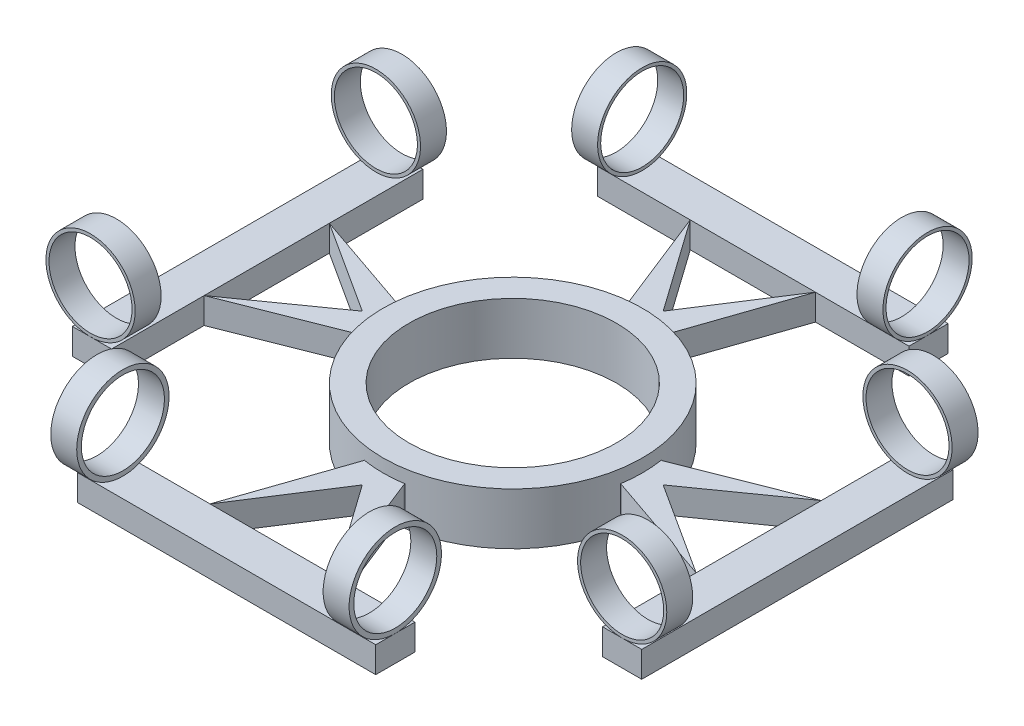
SolidWorks part; units mm, degrees
ref_plane "Front Plane" through (0, 0, 0) normal (0, 0, 1) x (1, 0, 0)
ref_plane "Top Plane" through (0, 0, 0) normal (0, 1, 0) x (1, 0, 0)
ref_plane "Right Plane" through (0, 0, 0) normal (1, 0, 0) x (0, 0, -1)
sketch "Sketch1" plane through (0, 0, 0) normal (0, 1, 0) x (1, 0, 0)
  circle A0 centre (0, 0) radius 2
  circle A1 centre (0, 0) radius 2.5
extrude "Boss-Extrude1" add sketch "Sketch1" along normal mid plane 1
sketch "Sketch3" plane through (0, 0, 0) normal (0, 1, 0) x (1, 0, 0)
  line L0 (-0.3997, 2.5) -> (-1.263, 4.6845)
  line L1 (-1.263, 4.6845) -> (0, 2.8997)
  line L2 (0, 2.8997) -> (1.1499, 4.6845)
  line L3 (1.1499, 4.6845) -> (0.3997, 2.5)
  line L4 (-2.5477, 4.6845) -> (-2.5477, 5.4386)
  line L5 (-2.5477, 5.4386) -> (2.4523, 5.4386)
  line L6 (-2.5477, 4.6845) -> (2.4523, 4.6845)
  line L7 (2.4523, 5.4386) -> (2.4523, 4.6845)
  line L8 (2.5, 0.3997) -> (4.6845, 1.263)
  line L9 (4.6845, 1.263) -> (2.8997, 0)
  line L10 (2.8997, 0) -> (4.6845, -1.1499)
  line L11 (4.6845, -1.1499) -> (2.5, -0.3997)
  line L12 (4.6845, 2.5477) -> (5.4386, 2.5477)
  line L13 (0.3997, -2.5) -> (1.263, -4.6845)
  line L14 (1.263, -4.6845) -> (0, -2.8997)
  line L15 (0, -2.8997) -> (-1.1499, -4.6845)
  line L16 (-1.1499, -4.6845) -> (-0.3997, -2.5)
  line L17 (2.5477, -4.6845) -> (2.5477, -5.4386)
  line L18 (-2.5, -0.3997) -> (-4.6845, -1.263)
  line L19 (-4.6845, -1.263) -> (-2.8997, 0)
  line L20 (-2.8997, 0) -> (-4.6845, 1.1499)
  line L21 (-4.6845, 1.1499) -> (-2.5, 0.3997)
  line L22 (-4.6845, -2.5477) -> (-5.4386, -2.5477)
  line L23 (5.4386, -2.4523) -> (4.6845, -2.4523)
  line L24 (4.6845, 2.5477) -> (4.6845, -2.4523)
  line L25 (4.6845, 2.5477) -> (5.4386, 2.5477)
  line L26 (5.4386, 2.5477) -> (5.4386, -2.4523)
  line L27 (-2.4523, -5.4386) -> (-2.4523, -4.6845)
  line L28 (2.5477, -4.6845) -> (-2.4523, -4.6845)
  line L29 (2.5477, -4.6845) -> (2.5477, -5.4386)
  line L30 (2.5477, -5.4386) -> (-2.4523, -5.4386)
  line L31 (-5.4386, 2.4523) -> (-4.6845, 2.4523)
  line L32 (-4.6845, -2.5477) -> (-4.6845, 2.4523)
  line L33 (-4.6845, -2.5477) -> (-5.4386, -2.5477)
  line L34 (-5.4386, -2.5477) -> (-5.4386, 2.4523)
  line L35 (2.5, -0.3997) -> (0, 0)
  line L36 (0, 0) -> (2.5, 0.3997)
  line L37 (0.3997, 2.5) -> (0, 0)
  line L38 (-0.3997, 2.5) -> (0, 0)
  line L39 (-2.5, 0.3997) -> (0, 0)
  line L40 (-2.5, -0.3997) -> (0, 0)
  line L41 (0.3997, -2.5) -> (0, 0)
  line L42 (-0.3997, -2.5) -> (0, 0)
  circle A9 centre (0, 0) radius 2.5
  circle A10 centre (0, 0) radius 2.5
  point P43 (0, 0)
  point P56 (0, 0)
  dimension "D1" = 5
  dimension "D2" = 4
  dimension "D4" = 0
  dimension "D3" = 4
extrude "Boss-Extrude2" add sketch "Sketch3" along normal mid plane 0.5 contours A10 L35 L11 L10 L9 L8 L36 | L26 L12 L24 L23 | A10 L42 L16 L15 L14 L13 L41 | L30 L17 L28 L27 | A10 L39 L21 L20 L19 L18 L40 | L7 L5 L4 L6 | A10 L37 L3 L2 L1 L0 L38 | L32 L31 L34 L33
sketch "Sketch4" plane through (2.5477, 0, 0) normal (1, 0, 0) x (0, 0, -1)
  line L0 (-5.4386, 0.25) -> (-5.4386, -0.25)
  line L1 (-5.4386, -0.25) -> (-4.6845, -0.25)
  line L2 (-4.6845, -0.25) -> (-4.6845, 0.25)
  line L3 (-4.6845, 0.25) -> (-5.4386, 0.25)
  circle A0 centre (-5.0616, 1.1405) radius 0.8905
  line M1 (-5.4386, -0.25) -> (-4.6845, -0.25)
  line M2 (-4.6845, -0.25) -> (-4.6845, 0.25)
  line M3 (-4.6845, 0.25) -> (-5.4386, 0.25)
  line M4 (-5.4386, 0.25) -> (-5.4386, -0.25)
extrude "Boss-Extrude3" add sketch "Sketch4" along normal mid plane 0.5 contours L3 M4 M1 M2 M3 | A0
sketch "Sketch5" plane through (-2.4523, 0, 0) normal (-1, 0, 0) x (0, 0, 1)
  line L4 (4.6845, -0.25) -> (5.4386, -0.25)
  line L5 (5.4386, -0.25) -> (5.4386, 0.25)
  line L6 (5.4386, 0.25) -> (4.6845, 0.25)
  line L7 (4.6845, 0.25) -> (4.6845, -0.25)
  line L8 (4.6845, -0.25) -> (5.4386, -0.25)
  line L9 (5.4386, -0.25) -> (5.4386, 0.25)
  line L10 (5.4386, 0.25) -> (4.6845, 0.25)
  line L11 (4.6845, 0.25) -> (4.6845, -0.25)
  circle A1 centre (5.0616, 1.1405) radius 0.8905
  circle A2 centre (5.0616, 1.1405) radius 0.8905
  line M6 (4.6845, -0.25) -> (5.4386, -0.25)
  line M7 (5.4386, -0.25) -> (5.4386, 0.25)
  line M8 (5.4386, 0.25) -> (4.6845, 0.25)
  line M9 (4.6845, 0.25) -> (4.6845, -0.25)
  dimension "D1" = 0
  dimension "D2" = 0
extrude "Boss-Extrude4" add sketch "Sketch5" along normal blind 0.5 contours A2 | L10 M9 M6 M7 M8
sketch "Sketch6" plane through (0, 0, 2.5477) normal (0, 0, 1) x (1, 0, 0)
  line L4 (-5.4386, -0.25) -> (-4.6845, -0.25)
  line L5 (-4.6845, -0.25) -> (-4.6845, 0.25)
  line L6 (-4.6845, 0.25) -> (-5.4386, 0.25)
  line L7 (-5.4386, 0.25) -> (-5.4386, -0.25)
  line L8 (-5.4386, -0.25) -> (-4.6845, -0.25)
  line L9 (-4.6845, -0.25) -> (-4.6845, 0.25)
  line L10 (-4.6845, 0.25) -> (-5.4386, 0.25)
  line L11 (-5.4386, 0.25) -> (-5.4386, -0.25)
  circle A0 centre (-5.0899, 1.11) radius 0.86
  line M5 (-5.4386, -0.25) -> (-4.6845, -0.25)
  line M6 (-4.6845, -0.25) -> (-4.6845, 0.25)
  line M7 (-4.6845, 0.25) -> (-5.4386, 0.25)
  line M8 (-5.4386, 0.25) -> (-5.4386, -0.25)
  dimension "D1" = 0
extrude "Boss-Extrude5" add sketch "Sketch6" along normal blind 0.5 contours A0 | L10 M8 M5 M6 M7
sketch "Sketch7" plane through (0, 0, -2.4523) normal (0, 0, -1) x (-1, 0, 0)
  line L4 (4.6845, -0.25) -> (5.4386, -0.25)
  line L5 (5.4386, -0.25) -> (5.4386, 0.25)
  line L6 (5.4386, 0.25) -> (4.6845, 0.25)
  line L7 (4.6845, 0.25) -> (4.6845, -0.25)
  line L8 (4.6845, -0.25) -> (5.4386, -0.25)
  line L9 (5.4386, -0.25) -> (5.4386, 0.25)
  line L10 (5.4386, 0.25) -> (4.6845, 0.25)
  line L11 (4.6845, 0.25) -> (4.6845, -0.25)
  circle A1 centre (5.0899, 1.11) radius 0.86
  circle A2 centre (5.0899, 1.11) radius 0.86
  line M6 (4.6845, -0.25) -> (5.4386, -0.25)
  line M7 (5.4386, -0.25) -> (5.4386, 0.25)
  line M8 (5.4386, 0.25) -> (4.6845, 0.25)
  line M9 (4.6845, 0.25) -> (4.6845, -0.25)
  dimension "D1" = 0
  dimension "D2" = 0
extrude "Boss-Extrude6" add sketch "Sketch7" along normal blind 0.5 contours A2 | L10 M9 M6 M7 M8
sketch "Sketch8" plane through (-2.9523, 0, 0) normal (-1, 0, 0) x (0, 0, 1)
  circle A0 centre (5.0616, 1.1405) radius 0.8
extrude "Cut-Extrude1" cut sketch "Sketch8" against normal through all
sketch "Sketch9" plane through (0, 0, 3.0477) normal (0, 0, 1) x (1, 0, 0)
  circle A0 centre (-5.0899, 1.11) radius 0.8
extrude "Cut-Extrude2" cut sketch "Sketch9" against normal through all
sketch "Sketch10" plane through (-2.5477, 0, 0) normal (-1, 0, 0) x (0, 0, 1)
  line L4 (-5.4386, -0.25) -> (-4.6845, -0.25)
  line L5 (-4.6845, -0.25) -> (-4.6845, 0.25)
  line L6 (-4.6845, 0.25) -> (-5.4386, 0.25)
  line L7 (-5.4386, 0.25) -> (-5.4386, -0.25)
  line L8 (-5.4386, -0.25) -> (-4.6845, -0.25)
  line L9 (-4.6845, -0.25) -> (-4.6845, 0.25)
  line L10 (-4.6845, 0.25) -> (-5.4386, 0.25)
  line L11 (-5.4386, 0.25) -> (-5.4386, -0.25)
  circle A0 centre (-5.0429, 1.11) radius 0.86
  line M5 (-5.4386, -0.25) -> (-4.6845, -0.25)
  line M6 (-4.6845, -0.25) -> (-4.6845, 0.25)
  line M7 (-4.6845, 0.25) -> (-5.4386, 0.25)
  line M8 (-5.4386, 0.25) -> (-5.4386, -0.25)
  dimension "D1" = 0
extrude "Boss-Extrude7" add sketch "Sketch10" along normal blind 0.5 contours L10 M8 M5 M6 M7 | A0
sketch "Sketch11" plane through (2.4523, 0, 0) normal (1, 0, 0) x (0, 0, -1)
  line L4 (4.6845, -0.25) -> (5.4386, -0.25)
  line L5 (5.4386, -0.25) -> (5.4386, 0.25)
  line L6 (5.4386, 0.25) -> (4.6845, 0.25)
  line L7 (4.6845, 0.25) -> (4.6845, -0.25)
  line L8 (4.6845, -0.25) -> (5.4386, -0.25)
  line L9 (5.4386, -0.25) -> (5.4386, 0.25)
  line L10 (5.4386, 0.25) -> (4.6845, 0.25)
  line L11 (4.6845, 0.25) -> (4.6845, -0.25)
  circle A1 centre (5.0429, 1.11) radius 0.86
  circle A2 centre (5.0429, 1.11) radius 0.86
  line M6 (4.6845, -0.25) -> (5.4386, -0.25)
  line M7 (5.4386, -0.25) -> (5.4386, 0.25)
  line M8 (5.4386, 0.25) -> (4.6845, 0.25)
  line M9 (4.6845, 0.25) -> (4.6845, -0.25)
  dimension "D1" = 0
  dimension "D2" = 0
extrude "Boss-Extrude8" add sketch "Sketch11" along normal blind 0.5 contours A2 | L10 M9 M6 M7 M8
sketch "Sketch12" plane through (0, 0, -2.5477) normal (0, 0, -1) x (-1, 0, 0)
  line L4 (-5.4386, -0.25) -> (-4.6845, -0.25)
  line L5 (-4.6845, -0.25) -> (-4.6845, 0.25)
  line L6 (-4.6845, 0.25) -> (-5.4386, 0.25)
  line L7 (-5.4386, 0.25) -> (-5.4386, -0.25)
  line L8 (-5.4386, -0.25) -> (-4.6845, -0.25)
  line L9 (-4.6845, -0.25) -> (-4.6845, 0.25)
  line L10 (-4.6845, 0.25) -> (-5.4386, 0.25)
  line L11 (-5.4386, 0.25) -> (-5.4386, -0.25)
  circle A0 centre (-5.0616, 1.11) radius 0.86
  dimension "D1" = 0
extrude "Boss-Extrude9" add sketch "Sketch12" along normal blind 0.5 contours A0 | L8 L9 L10 L11
sketch "Sketch13" plane through (0, 0, 2.4523) normal (0, 0, 1) x (1, 0, 0)
  line L4 (4.6845, -0.25) -> (5.4386, -0.25)
  line L5 (5.4386, -0.25) -> (5.4386, 0.25)
  line L6 (5.4386, 0.25) -> (4.6845, 0.25)
  line L7 (4.6845, 0.25) -> (4.6845, -0.25)
  line L8 (4.6845, -0.25) -> (5.4386, -0.25)
  line L9 (5.4386, -0.25) -> (5.4386, 0.25)
  line L10 (5.4386, 0.25) -> (4.6845, 0.25)
  line L11 (4.6845, 0.25) -> (4.6845, -0.25)
  circle A1 centre (5.0616, 1.11) radius 0.86
  circle A2 centre (5.0616, 1.11) radius 0.86
  dimension "D1" = 0
  dimension "D2" = 0
extrude "Boss-Extrude10" add sketch "Sketch13" along normal blind 0.5 contours A2 | L10 L11 L8 L9
sketch "Sketch14" plane through (0, 0, 2.9523) normal (0, 0, 1) x (1, 0, 0)
  circle A0 centre (5.0616, 1.11) radius 0.8
extrude "Cut-Extrude3" cut sketch "Sketch14" against normal through all
sketch "Sketch15" plane through (2.9523, 0, 0) normal (1, 0, 0) x (0, 0, -1)
  circle A0 centre (5.0429, 1.11) radius 0.8
extrude "Cut-Extrude4" cut sketch "Sketch15" against normal through all
